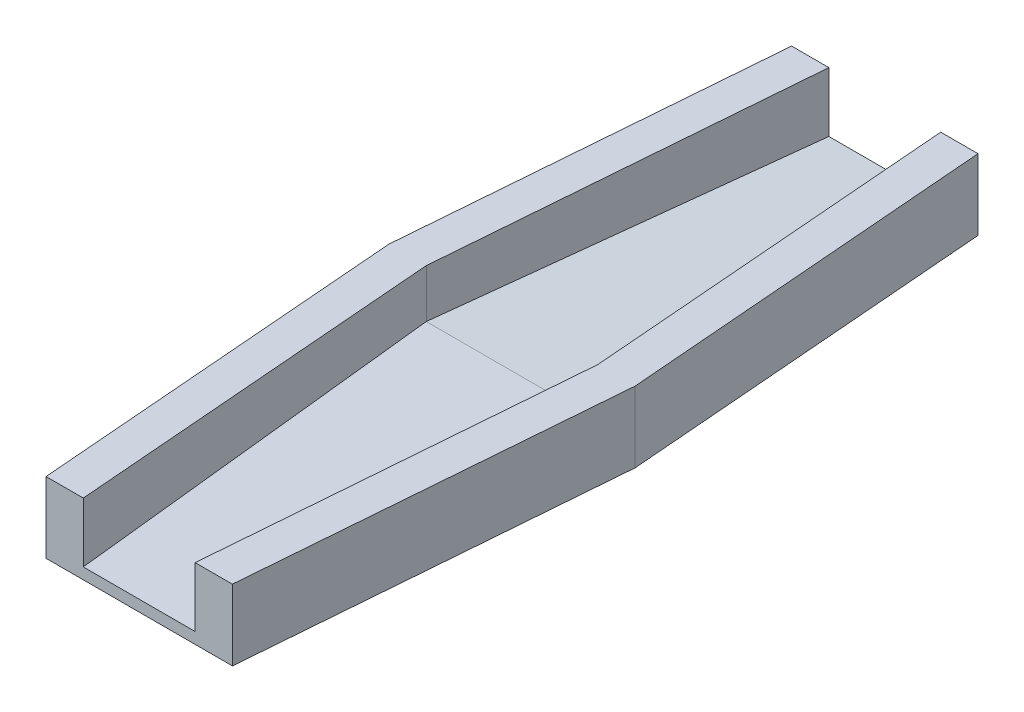
SolidWorks part; units mm, degrees
ref_plane "Plano frontal" through (0, 0, 0) normal (0, 0, 1) x (1, 0, 0)
ref_plane "Plano superior" through (0, 0, 0) normal (0, 1, 0) x (1, 0, 0)
ref_plane "Plano direito" through (0, 0, 0) normal (1, 0, 0) x (0, 0, -1)
sketch "Esboço1" plane through (0, 0, 0) normal (0, 0, 1) x (1, 0, 0)
  line L1 (-3.3, -1.9) -> (3.3, -1.9)
  line L2 (-3.3, -1.9) -> (-3.3, 1.9)
  line L3 (-3.3, 1.9) -> (3.3, 1.9)
  line L4 (3.3, -1.9) -> (3.3, 1.9)
  line L5 (-3.3, -1.9) -> (3.3, 1.9) construction
  line L6 (-3.3, 1.9) -> (3.3, -1.9) construction
  point P0 (0, 0)
  dimension "D1" = 6.6
  dimension "D2" = 3.8
ref_plane "Plano1" through (0, 0, 10) normal (0, 0, 1) x (1, 0, 0)
sketch "Esboço2" plane through (0, 0, 10) normal (0, 0, 1) x (1, 0, 0)
  line L1 (-2.5, -1.9) -> (2.5, -1.9)
  line L2 (-2.5, -1.9) -> (-2.5, 1.9)
  line L3 (-2.5, 1.9) -> (2.5, 1.9)
  line L4 (2.5, -1.9) -> (2.5, 1.9)
  line L5 (-2.5, -1.9) -> (2.5, 1.9) construction
  line L6 (-2.5, 1.9) -> (2.5, -1.9) construction
  point P0 (0, 0)
  dimension "D1" = 5
  dimension "D2" = 3.8
loft "Loft1" add profiles "Esboço1", "Esboço2"
sketch "Esboço3" plane through (0, 0, 0) normal (0, 0, 1) x (1, 0, 0)
  line L1 (-4.3618, 0) -> (6.3395, 0)
  line L2 (-4.3618, 0) -> (-4.3618, 3.7794)
  line L3 (-4.3618, 3.7794) -> (6.3395, 3.7794)
  line L4 (6.3395, 0) -> (6.3395, 3.7794)
  point P4 (6.3395, 3.7794)
extrude "Corte Meio" cut sketch "Esboço3" along normal blind 80
ref_plane "Plano2" through (0, 0, 0) normal (0, 0, 1) x (1, 0, 0)
sketch "Esboço5" plane through (0, 0, 0) normal (0, 0, 1) x (1, 0, 0)
  line L1 (2.3, -1.3) -> (-2.3, -1.3)
  line L2 (2.3, -1.3) -> (2.3, 1.3)
  line L3 (2.3, 1.3) -> (-2.3, 1.3)
  line L4 (-2.3, -1.3) -> (-2.3, 1.3)
  line L5 (2.3, -1.3) -> (-2.3, 1.3) construction
  line L6 (2.3, 1.3) -> (-2.3, -1.3) construction
  point P0 (0, 0)
  dimension "D1" = 4.6
  dimension "D2" = 2.6
sketch "Esboço6" plane through (0, 0, 10) normal (0, 0, 1) x (1, 0, 0)
  line L1 (-1.5, -1.6) -> (1.5, -1.6)
  line L2 (-1.5, -1.6) -> (-1.5, 1.6)
  line L3 (-1.5, 1.6) -> (1.5, 1.6)
  line L4 (1.5, -1.6) -> (1.5, 1.6)
  line L5 (-1.5, -1.6) -> (1.5, 1.6) construction
  line L6 (-1.5, 1.6) -> (1.5, -1.6) construction
  line L7 (2.5, 0) -> (-2.5, 0) construction
  point P0 (0, 0)
  dimension "D1" = 3.2
  dimension "D2" = 0
  dimension "D3" = 3
loft "Loft de corte1" cut profiles "Esboço6", "Esboço5"
mirror "Espelhar1" about plane through (0, 0, 0) normal (0, 0, 1) of "Loft1"
mirror "Espelhar2" about plane through (0, 0, 0) normal (0, 0, 1) of "Corte Meio"
mirror "Espelhar3" about plane through (0, 0, 0) normal (0, 0, 1) of "Loft de corte1"
